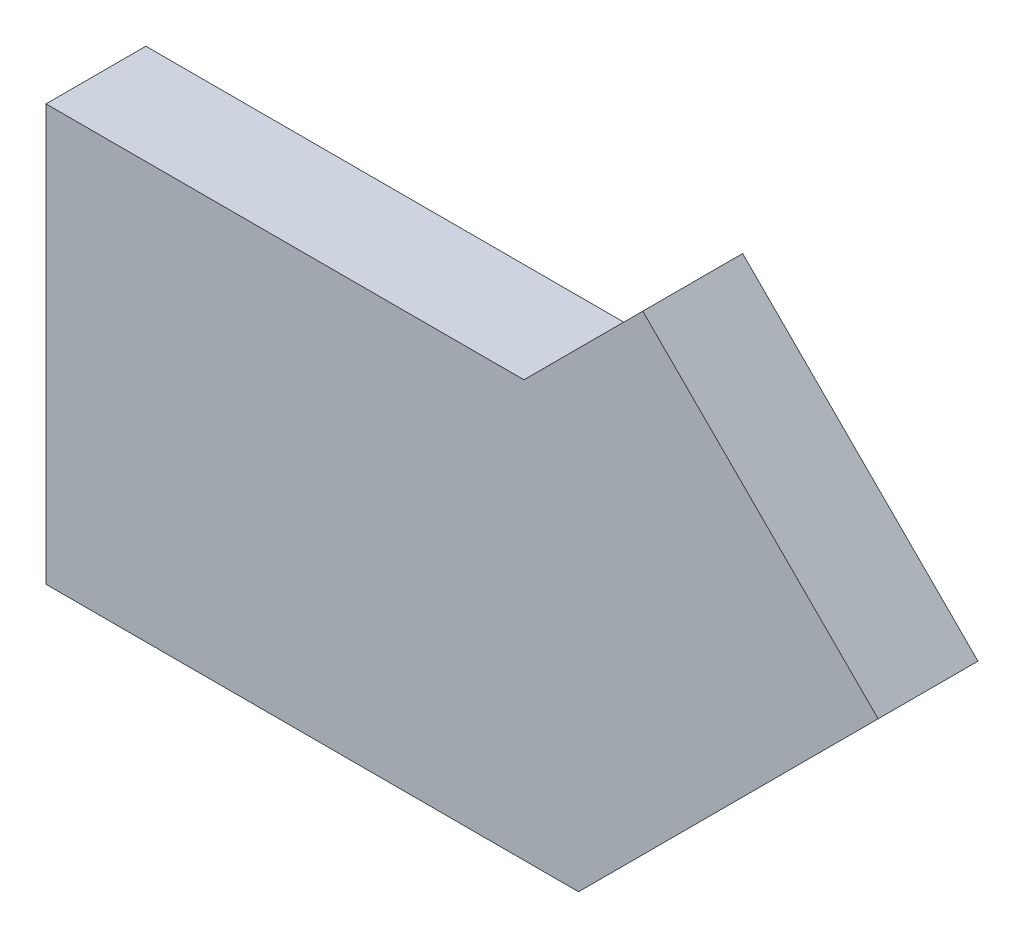
SolidWorks part; units mm, degrees
ref_plane "前基準面" through (0, 0, 0) normal (0, 0, 1) x (1, 0, 0)
ref_plane "上基準面" through (0, 0, 0) normal (0, 1, 0) x (1, 0, 0)
ref_plane "右基準面" through (0, 0, 0) normal (1, 0, 0) x (0, 0, -1)
sketch "草圖1" plane through (0, 0, 0) normal (0, 0, 1) x (1, 0, 0)
  line L0 (0, 0) -> (32, 0)
  line L1 (32, 0) -> (50, 18)
  line L2 (50, 18) -> (35.8579, 32.1421)
  line L3 (35.8579, 32.1421) -> (28.7157, 25)
  line L4 (28.7157, 25) -> (0, 25)
  line L5 (0, 25) -> (0, 0)
  dimension "D1" = 20
  dimension "D2" = 32
  dimension "D3" = 25
  dimension "D4" = 50
  dimension "D5" = 135
extrude "填料-伸長1" add sketch "草圖1" along normal blind 6
